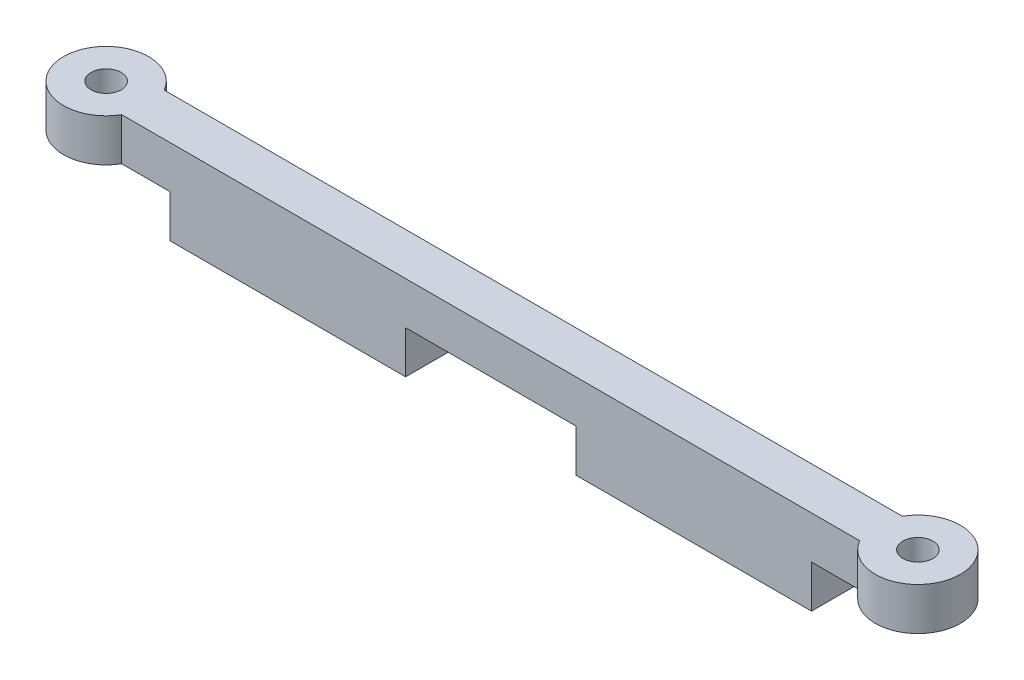
SolidWorks part; units mm, degrees
ref_plane "Front Plane" through (0, 0, 0) normal (0, 0, 1) x (1, 0, 0)
ref_plane "Top Plane" through (0, 0, 0) normal (0, 1, 0) x (1, 0, 0)
ref_plane "Right Plane" through (0, 0, 0) normal (1, 0, 0) x (0, 0, -1)
sketch "Sketch1" plane through (0, 0, 0) normal (0, 1, 0) x (1, 0, 0)
  line L0 (0, 0) -> (121.158, 0)
  line L1 (121.158, 0) -> (121.158, 3.175)
  line L2 (121.158, 3.175) -> (0, 3.175)
  line L3 (0, 3.175) -> (0, -3.175)
  line L4 (0, -3.175) -> (121.158, -3.175)
  circle A0 centre (0, 0) radius 2.2479
  circle A1 centre (0, 0) radius 3.175
  circle A2 centre (0, 0) radius 6.35
  circle A3 centre (121.158, 0) radius 2.2479
  circle A4 centre (121.158, 0) radius 3.175
  circle A5 centre (121.158, 0) radius 6.35
  dimension "D1" = 4.4958
  dimension "D2" = 6.35
  dimension "D3" = 12.7
  dimension "D4" = 4.4958
  dimension "D5" = 6.35
  dimension "D6" = 12.7
  dimension "D7" = 121.158
extrude "Boss-Extrude1" add sketch "Sketch1" along normal blind 12.7 contours L3 A1 A0 | L2 A2 L4 A1 | L0 A1 L3 A0 | L3 A1 L0 A0 | L0 A2 L2 A1 | L4 A2 L0 A1 | A5 L2 A2 L0 | A5 L0 A2 L4 | L2 A5 L0 A4 | L0 A5 L4 A4 | L1 A4 L0 A3 | A4 L1 A3 L0 | L4 A5 L2 A4
sketch "Sketch2" plane through (0, 0, 0) normal (0, -1, 0) x (1, 0, 0)
  line L0 (0, 0) -> (12.7, 0) construction
  line L1 (12.7, 0) -> (12.7, 3.175) construction
  line L2 (5.4993, 3.175) -> (115.6587, 3.175) construction
  line L3 (121.158, 0) -> (108.458, 0) construction
  line L4 (108.458, 0) -> (108.458, 3.175) construction
  line L5 (108.458, 3.175) -> (108.458, -3.175)
  line L6 (108.458, 3.175) -> (118.6418, 3.175)
  line L7 (108.458, -3.175) -> (118.6418, -3.175)
  line L8 (118.6418, 3.175) -> (118.6418, -3.175)
  line L9 (115.6587, -3.175) -> (5.4993, -3.175) construction
  line L10 (12.7, 3.175) -> (12.7, -3.175)
  line L11 (12.7, 3.175) -> (2.6541, 3.175)
  line L12 (12.7, -3.175) -> (2.6541, -3.175)
  line L13 (2.6541, 3.175) -> (2.6541, -3.175)
  circle A0 centre (0, 0) radius 6.35
  circle A1 centre (121.158, 0) radius 6.35
  circle M3 centre (121.158, 0) radius 2.2479
  arc M4 (115.6587, -3.175) -> (115.6587, 3.175) centre (121.158, 0) ccw
  line M5 (115.6587, 3.175) -> (5.4993, 3.175)
  arc M6 (5.4993, 3.175) -> (5.4993, -3.175) centre (0, 0) ccw
  line M7 (5.4993, -3.175) -> (115.6587, -3.175)
  circle M8 centre (0, 0) radius 2.2479
  dimension "D1" = 12.7
  dimension "D2" = 12.7
extrude "Cut-Extrude1" cut sketch "Sketch2" against normal blind 6.35 contours A0 L10 M7 M5 | L12 A0 L11 L13 | L13 L11 L12 M6 M8 | L6 L8 L7 M4 M3 | A1 L5 M5 M7 | L6 A1 L7 L8
sketch "Sketch3" plane through (0, 0, 0) normal (0, -1, 0) x (1, 0, 0)
  line L0 (47.879, 3.175) -> (47.879, -3.175)
  line L1 (47.879, 3.175) -> (73.279, 3.175)
  line L2 (47.879, -3.175) -> (73.279, -3.175)
  line L3 (73.279, 3.175) -> (73.279, -3.175)
  line L4 (12.7, 3.175) -> (108.458, 3.175) construction
  line L5 (108.458, -3.175) -> (12.7, -3.175) construction
  line L6 (12.7, 3.175) -> (12.7, -3.175) construction
  dimension "D1" = 25.4
  dimension "D2" = 35.179
extrude "Cut-Extrude2" cut sketch "Sketch3" against normal blind 6.35
